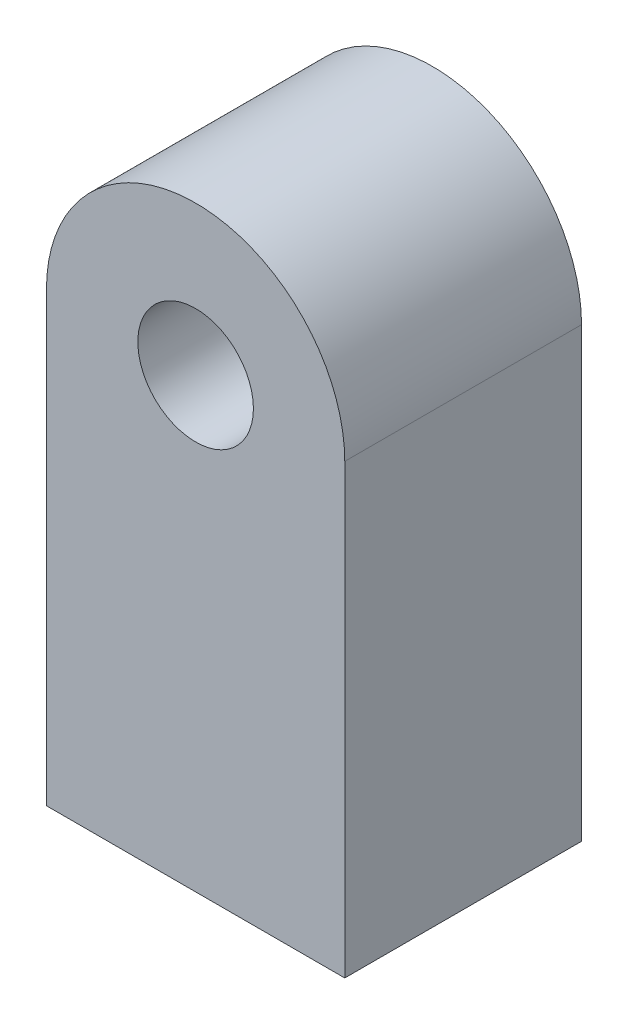
SolidWorks part; units mm, degrees
ref_plane "Front Plane" through (0, 0, 0) normal (0, 0, 1) x (1, 0, 0)
ref_plane "Top Plane" through (0, 0, 0) normal (0, 1, 0) x (1, 0, 0)
ref_plane "Right Plane" through (0, 0, 0) normal (1, 0, 0) x (0, 0, -1)
sketch "Sketch1" plane through (0, 0, 0) normal (0, 0, 1) x (1, 0, 0)
  line L1 (-4, 0) -> (4, 0)
  line L2 (-4, 0) -> (-4, 12)
  line L4 (4, 0) -> (4, 12)
  arc A0 (-4, 12) -> (4, 12) centre (0, 12) cw
  circle A1 centre (0, 12) radius 1.55
  point P4 (0, 0)
  dimension "D3" = 3.1
  dimension "D1" = 8
  dimension "D2" = 12
extrude "Boss-Extrude1" add sketch "Sketch1" along normal blind 6.35
